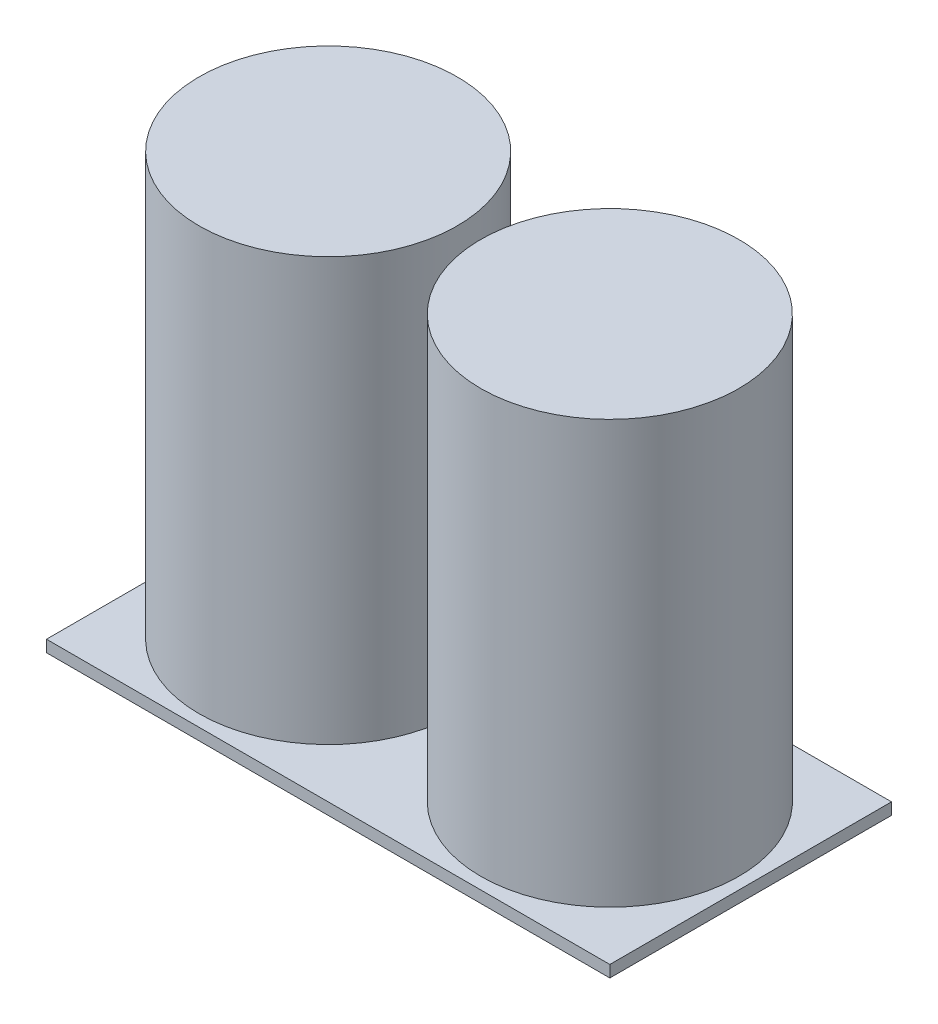
SolidWorks part; units mm, degrees
ref_plane "Front" through (0, 0, 0) normal (0, 0, 1) x (1, 0, 0)
ref_plane "Top" through (0, 0, 0) normal (0, 1, 0) x (1, 0, 0)
ref_plane "Right" through (0, 0, 0) normal (1, 0, 0) x (0, 0, -1)
sketch "Sketch1" plane through (0, 0, 0) normal (0, 1, 0) x (1, 0, 0)
  line L0 (0, 0) -> (-609.6, 0) construction
  line L1 (-609.6, 304.8) -> (609.6, 304.8)
  line L2 (-609.6, 304.8) -> (-609.6, -304.8)
  line L3 (-609.6, -304.8) -> (609.6, -304.8)
  line L4 (609.6, 304.8) -> (609.6, -304.8)
  line L5 (-609.6, 304.8) -> (609.6, -304.8) construction
  line L6 (-609.6, -304.8) -> (609.6, 304.8) construction
  line L7 (0, 0) -> (609.6, 0) construction
  point P0 (0, 0)
  dimension "D1" = 1219.2
  dimension "D2" = 609.6
extrude "Boss-Extrude1" add sketch "Sketch1" along normal blind 25.4
sketch "Sketch2" plane through (0, 25.4, 0) normal (0, 1, 0) x (1, 0, 0)
  line L0 (0, 0) -> (-609.6, 0) construction
  line L1 (-609.6, 304.8) -> (-609.6, -304.8) construction
  line L2 (0, 0) -> (609.6, 0) construction
  line L3 (609.6, -304.8) -> (609.6, 304.8) construction
  circle A0 centre (-304.8, 0) radius 279.4
  circle A1 centre (304.8, 0) radius 279.4
  dimension "D1" = 558.8
extrude "Boss-Extrude2" add sketch "Sketch2" along normal blind 914.4
